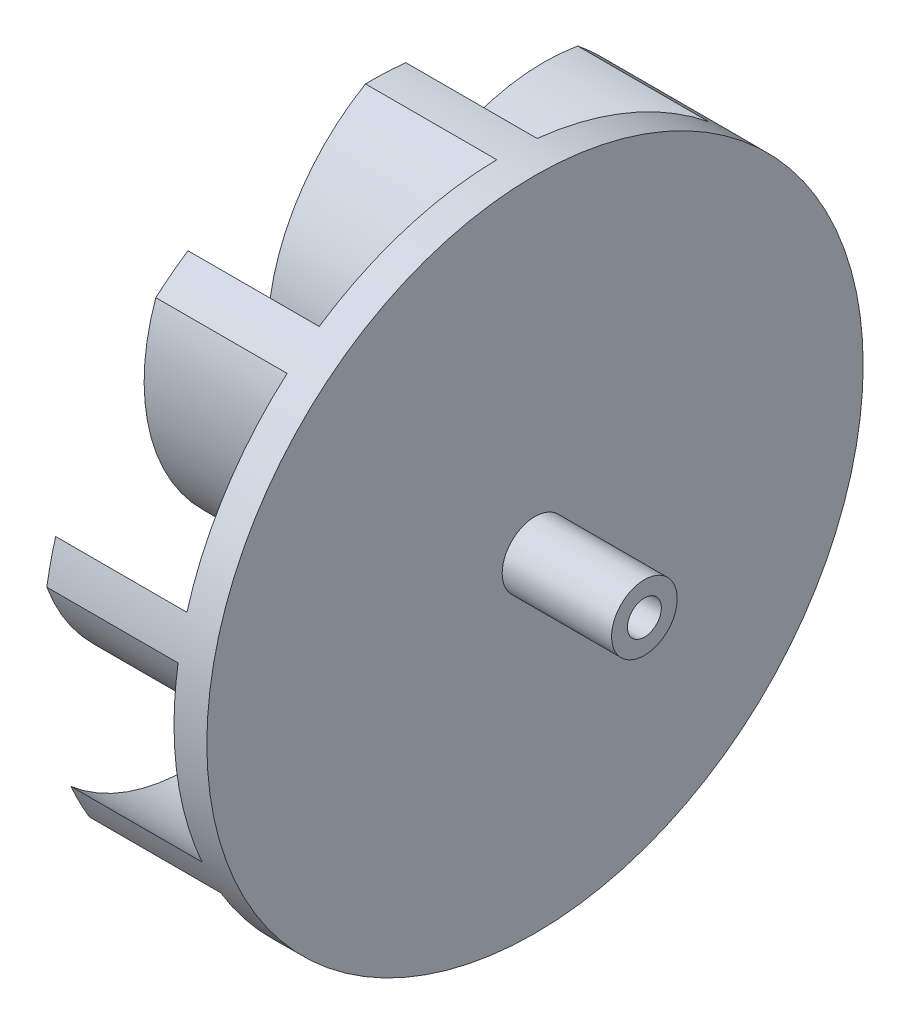
SolidWorks part; units mm, degrees
ref_plane "Front Plane" through (0, 0, 0) normal (0, 0, 1) x (1, 0, 0)
ref_plane "Top Plane" through (0, 0, 0) normal (0, 1, 0) x (1, 0, 0)
ref_plane "Right Plane" through (0, 0, 0) normal (1, 0, 0) x (0, 0, -1)
sketch "Sketch1" plane through (0, 0, 0) normal (0, 1, 0) x (1, 0, 0)
  line L0 (0, 0) -> (0, 30)
  line L1 (0, 30) -> (-3, 30)
  line L2 (-3, 30) -> (-3, 5)
  line L3 (-3, 5) -> (-8, 5)
  line L4 (-12, 1) -> (-12, 0)
  line L5 (-12, 0) -> (0, 0)
  arc A0 (-8, 5) -> (-12, 1) centre (-8, 1) ccw
  point P9 (-12, 5)
  dimension "D5" = 4
  dimension "D1" = 30
  dimension "D2" = 3
  dimension "D3" = 12
  dimension "D4" = 5
revolve "Revolve1" add sketch "Sketch1" angle 360 about L5
sketch "Sketch2" plane through (-3, 0, 0) normal (-1, 0, 0) x (0, 0, 1)
  line L0 (0, 0) -> (0, 30) construction
  line L1 (0, 0) -> (-8.1317, 8.1317) construction
  arc A0 (-6.7408, 9.3173) -> (-8.1317, 8.1317) centre (0, 0) ccw
  circle A1 centre (0, 0) radius 30 construction
  arc A2 (0, 30) -> (-8.1317, 8.1317) centre (8.7827, 14.2881) ccw
  arc A3 (3.6902, 29.7722) -> (-6.7408, 9.3173) centre (8.7827, 14.2881) ccw
  arc A4 (3.6902, 29.7722) -> (0, 30) centre (0, 0) ccw
  arc A5 (0.8295, 28.5161) -> (-6.5343, 8.7132) centre (8.7827, 14.2881) ccw construction
  dimension "D1" = 23
  dimension "D3" = 18
  dimension "D2" = 45
  dimension "D4" = 1.7
extrude "Boss-Extrude1" [suppressed] add sketch "Sketch2" along normal blind 12
pattern_circular "CirPattern1" [suppressed] count 8 over 360
sketch "Sketch4" plane through (0, 0, 0) normal (1, 0, 0) x (0, 0, -1)
  circle A0 centre (0, 0) radius 3
  dimension "D1" = 6
extrude "Boss-Extrude2" add sketch "Sketch4" along normal blind 10
sketch "Sketch5" plane through (10, 0, 0) normal (1, 0, 0) x (0, 0, -1)
  circle A0 centre (0, 0) radius 1.55
  dimension "D1" = 3.1
extrude "Cut-Extrude1" cut sketch "Sketch5" against normal blind 11.4
sketch "Sketch6" plane through (-3, 0, 0) normal (-1, 0, 0) x (0, 0, 1)
  line L0 (0, 0) -> (0.4979, 29.9959) construction
  line L1 (0, 0) -> (8.2656, 7.9957) construction
  arc A0 (8.2656, 7.9957) -> (6.8945, 9.2041) centre (0, 0) ccw
  circle A1 centre (0, 0) radius 30 construction
  arc A2 (0.4979, 29.9959) -> (8.2656, 7.9957) centre (-8.5444, 14.4319) cw
  arc A3 (-3.1956, 29.8293) -> (6.8945, 9.2041) centre (-8.5444, 14.4319) cw
  arc A4 (-0.3561, 28.5259) -> (6.6779, 8.6035) centre (-8.5444, 14.4319) cw construction
  arc A5 (0.4979, 29.9959) -> (-3.1956, 29.8293) centre (0, 0) ccw
  dimension "D1" = 23
  dimension "D3" = 18
  dimension "D2" = 45
  dimension "D4" = 1.7
extrude "Boss-Extrude3" add sketch "Sketch6" along normal blind 12
pattern_circular "CirPattern2" count 9 over 360 about axis through (0, 0, 0) along (1, 0, 0) of "Boss-Extrude3"
